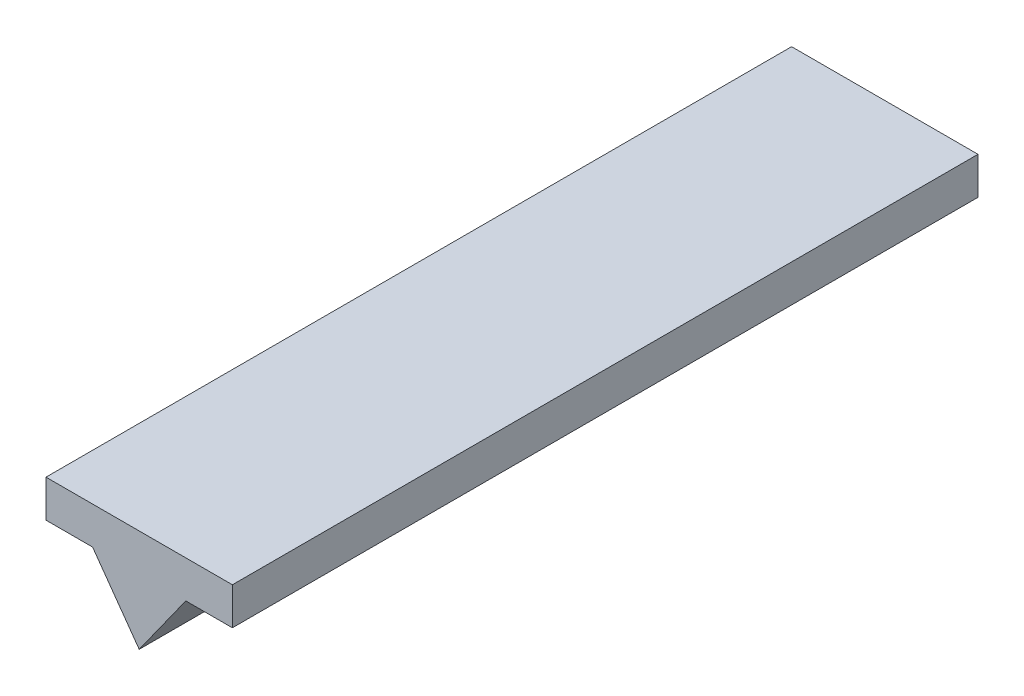
SolidWorks part; units mm, degrees
ref_plane "Front Plane" through (0, 0, 0) normal (0, 0, 1) x (1, 0, 0)
ref_plane "Top Plane" through (0, 0, 0) normal (0, 1, 0) x (1, 0, 0)
ref_plane "Right Plane" through (0, 0, 0) normal (1, 0, 0) x (0, 0, -1)
sketch "Sketch1" plane through (0, 0, 0) normal (0, 0, 1) x (1, 0, 0)
  line L0 (0, 0) -> (2, 0)
  line L1 (2, 0) -> (2, -0.4)
  line L2 (2, -0.4) -> (1.5, -0.4)
  line L3 (1.5, -0.4) -> (1, -1.1)
  line L4 (1, -1.1) -> (0.5, -0.4)
  line L5 (0.5, -0.4) -> (0, -0.4)
  line L6 (0, -0.4) -> (0, 0)
  point P6 (0.9028, -0.8564)
  point P9 (0, 0)
  dimension "D1" = 2
  dimension "D2" = 1
  dimension "D3" = 0.4
  dimension "D4" = 0.7
extrude "Boss-Extrude1" add sketch "Sketch1" along normal blind 8
